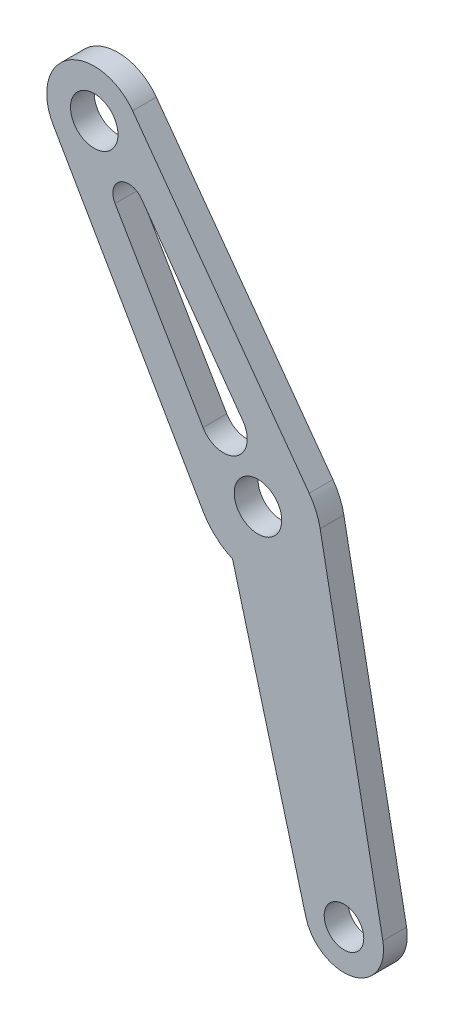
SolidWorks part; units mm, degrees
ref_plane "前视" through (0, 0, 0) normal (0, 0, 1) x (1, 0, 0)
ref_plane "上视" through (0, 0, 0) normal (0, 1, 0) x (1, 0, 0)
ref_plane "右视" through (0, 0, 0) normal (1, 0, 0) x (0, 0, -1)
sketch "草图1" plane through (0, 0, 0) normal (0, 0, 1) x (1, 0, 0)
  line L0 (0, -66.88) -> (0, 70.0366) construction
  line L1 (-82.071, 0) -> (84.4384, 0) construction
  line L2 (0, 0) -> (-23.5472, 87.8792) construction
  line L3 (-10.8704, 40.5689) -> (-81.269, 148.9732) construction
  line L4 (-36.7637, 69.4399) -> (-17.7998, 36.5709)
  line L5 (-26.7136, 75.9665) -> (-4.3997, 45.2731)
  line L6 (-14.0837, 33.2426) -> (-4.8296, -1.2941)
  line L7 (4.9097, 0.9458) -> (-3.0148, 42.0822)
  line L8 (-28.9347, 64.7171) -> (-17.8152, 45.7604)
  line L10 (-25.5835, 66.8934) -> (-12.7884, 49.0248)
  circle A0 centre (0, 0) radius 2.5
  circle A1 centre (-10.8704, 40.5689) radius 3
  circle A2 centre (-31.5667, 72.4384) radius 3
  arc A3 (-26.7136, 75.9665) -> (-36.7637, 69.4399) centre (-31.5667, 72.4384) ccw
  arc A4 (-4.8296, -1.2941) -> (4.9097, 0.9458) centre (0, 0) ccw
  arc A5 (-17.7998, 36.5709) -> (-14.0837, 33.2426) centre (-10.8704, 40.5689) ccw
  arc A6 (-3.0148, 42.0822) -> (-4.3997, 45.2731) centre (-10.8704, 40.5689) ccw
  arc A7 (-25.5835, 66.8934) -> (-28.9347, 64.7171) centre (-27.2096, 65.729) ccw
  arc A8 (-17.8152, 45.7604) -> (-13.2795, 49.5597) centre (-15.2275, 47.2782) ccw
  dimension "D2" = 33
  dimension "D5" = 5
  dimension "D6" = 6
  dimension "D7" = 6
  dimension "D8" = 12
  dimension "D9" = 16
  dimension "D10" = 5
  dimension "D12" = 8
  dimension "D14" = 4
  dimension "D15" = 6
  dimension "D1" = 15
  dimension "D3" = 42
  dimension "D4" = 38
  dimension "D11" = 5
  dimension "D13" = 8
extrude "凸台-拉伸1" add sketch "草图1" along normal blind 3 contours L7 A6 L5 A3 L4 A5 L6 A4 A8 L8 A7 L10 A0 A1 A2
